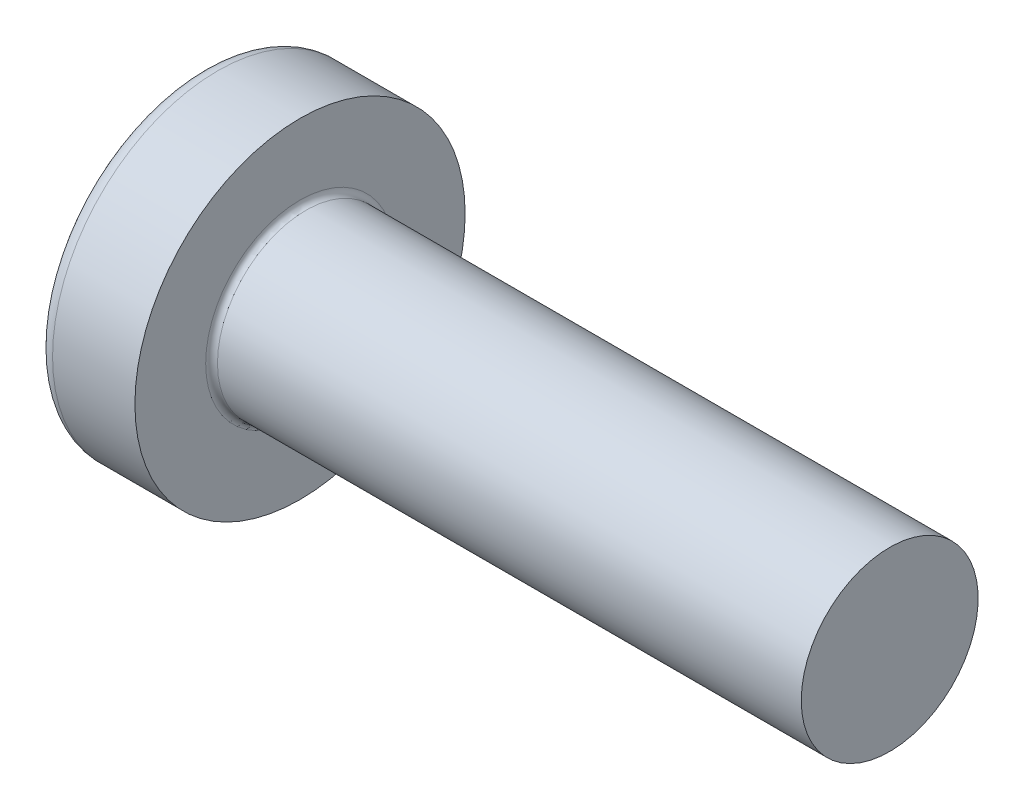
SolidWorks part; units mm, degrees
ref_plane "Plane1" through (0, 0, 0) normal (0, 0, 1) x (1, 0, 0)
ref_plane "Plane2" through (0, 0, 0) normal (0, 1, 0) x (1, 0, 0)
ref_plane "Plane3" through (0, 0, 0) normal (1, 0, 0) x (0, 0, -1)
sketch "BodySke" plane through (0, 0, 0) normal (0, 0, 1) x (1, 0, 0)
  line L0 (2.4, 1.5) -> (2.4, 2.8)
  line L1 (2.65, 6.35) -> (2.65, -3.175) construction
  line L2 (-25.4, 0) -> (127, 0) construction
  line L3 (12.4, 0) -> (0, 0)
  line L4 (2.4, 1.5) -> (12.4, 1.5)
  line L5 (12.4, 1.5) -> (12.4, 0)
  line L6 (1.0035, 2.8) -> (2.4, 2.8)
  line L8 (2.4, 6.35) -> (2.4, -3.175) construction
  arc A0 (0.7754, 2.6744) -> (0, 0) centre (5, 0) ccw
  arc A2 (0.7754, 2.6744) -> (1.0035, 2.8) centre (1.0035, 2.53) cw
  dimension "Head_crown_rad" = 5
  dimension "Head_fillet_rad" = 0.27
  dimension "Length" = 10
  dimension "Head_ht" = 2.4
  dimension "Head_dia" = 5.6
  dimension "Advance" = 0.5
  dimension "Thread_nom" = 10
  dimension "Diameter" = 3
revolve "Base-Revolve" add sketch "BodySke"
cosmetic thread "ThreadCosmetic" [suppressed]
fillet "Fillet1" radius 0.1 1 edges at (2.4, 0, 1.5)
sketch "Sketch3" plane through (0, 0, 0) normal (1, 0, 0) x (0, 0, -1)
  line L0 (0.37, -1.4) -> (-0.37, -1.4)
  line L1 (0.37, -1.4) -> (0.37, 1.4)
  line L2 (-0.37, 1.4) -> (0.37, 1.4)
  line L3 (-0.37, 1.4) -> (-0.37, -1.4)
  dimension "Cross_dia" = 2.8
  dimension "D1" = 1.4
  dimension "Cross_width" = 0.74
  dimension "D2" = 0.37
ref_plane "Plane4" through (1.75, 0, 0) normal (1, 0, 0) x (0, 0, -1)
sketch "Sketch4" plane through (1.75, 0, 0) normal (1, 0, 0) x (0, 0, -1)
  line L0 (0.37, -0.5275) -> (-0.37, -0.5275)
  line L1 (0.37, -0.5275) -> (0.37, 0.5275)
  line L2 (-0.37, 0.5275) -> (0.37, 0.5275)
  line L3 (-0.37, 0.5275) -> (-0.37, -0.5275)
  dimension "D1" = 0.74
  dimension "D2" = 1.055
  dimension "D3" = 0.37
  dimension "D4" = 0.5275
loft "Recess" cut profiles "Sketch3", "Sketch4"
pattern_circular "RecPat" count 2 every 90 about axis through (0, 0, 0) along (1, 0, 0) of "Recess"
sketch "RecCorSke" plane through (0, 0, 0) normal (0, 0, 1) x (1, 0, 0)
  line L0 (-3.175, 0) -> (15.875, 0) construction
  line L1 (-25.4, 0) -> (127, 0) construction
  line L2 (0, 0) -> (0, 0.6784)
  line L3 (0, 0.6784) -> (1.75, 0.556)
  line L4 (1.75, 0.556) -> (1.9307, 0)
  line L5 (1.9307, 0) -> (0, 0)
  dimension "Diameter" = 1.112
  dimension "Depth" = 1.75
  dimension "Draft_angle" = 4
  dimension "Bottom_angle" = 18
revolve "RecessCore" cut sketch "RecCorSke" angle 360 about L0
sketch "ThdSchSke" plane through (0, 0, 0) normal (0, 0, 1) x (1, 0, 0)
  line L0 (3.4, -1.2195) -> (3.2036, -1.5)
  line L1 (3.4, -1.2195) -> (3.5964, -1.5)
  line L2 (3.5964, -1.5) -> (3.5964, -1.875)
  line L3 (-3.175, 0) -> (5.1513, 0) construction
  line L5 (3.5964, -1.875) -> (3.2036, -1.875)
  line L6 (3.2036, -1.875) -> (3.2036, -1.5)
  dimension "Diameter" = 3
  dimension "SideAngle" = 55
  dimension "VeeAngle" = 70
  dimension "Thread_minor" = 2.439
  dimension "Overcut" = 3.75
  dimension "Start" = 3.4
revolve "ThreadSchematic" [suppressed] cut sketch "ThdSchSke" angle 360 about L3
pattern_linear "ThdSchPat" [suppressed]
equation "\"D1@Sketch3\" = \"Cross_dia@Sketch3\" / 2"
equation "\"D2@Sketch3\" = \"Cross_width@Sketch3\" / 2"
equation "\"Depth@RecCorSke\" = \"Cross_depth@Plane4\""
equation "\"D1@Sketch4\" = \"Cross_width@Sketch3\""
equation "\"D2@Sketch4\" = \"Cross_dia@Sketch3\" - 2.0 * \"Cross_depth@Plane4\" * tan(26.5  * 0.017453292)"
equation "\"D3@Sketch4\" = \"D1@Sketch4\" / 2"
equation "\"D4@Sketch4\" = \"D2@Sketch4\" / 2"
equation "\"Thread_length@ThreadCosmetic\" = ((sgn( (\"Length@BodySke\" - \"Advance@BodySke\" * 2.0 ) - \"Thread_nom@BodySke\" )-1)*( (\"Length@BodySke\" - \"Advance@BodySke\" * 2.0 ) - \"Thread_nom@BodySke\" ))/-2+ \"Thread_nom@BodySke\""
equation "\"Thread_minor@ThdSchSke\" = \"Thread_minor@ThreadCosmetic\""
equation "\"Diameter@ThdSchSke\" = \"Diameter@BodySke\""
equation "\"Overcut@ThdSchSke\" = \"Diameter@BodySke\" * 1.25"
equation "\"Start@ThdSchSke\" = \"Head_ht@BodySke\" + \"Length@BodySke\" - \"Thread_length@ThreadCosmetic\"  '---Non-countersunk---"
equation "\"Num_threads@ThdSchPat\" = int( \"Thread_length@ThreadCosmetic\" / \"Advance@BodySke\" + 0.999 )  + 1"
equation "\"Advance@ThdSchPat\" = \"Thread_length@ThreadCosmetic\" /  (\"Num_threads@ThdSchPat\" - 1) 'relax it"
